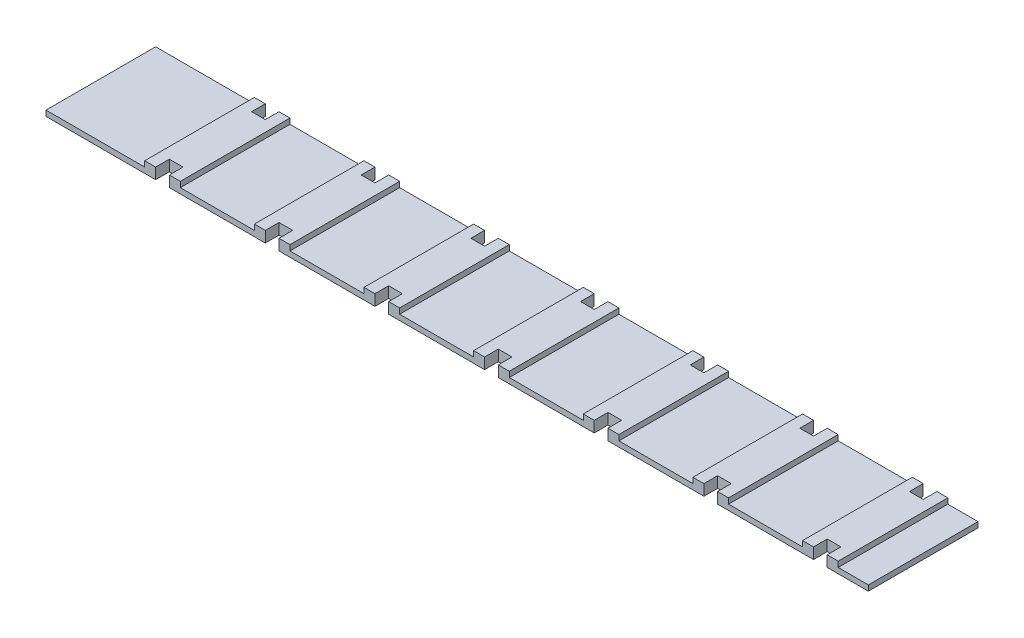
SolidWorks part; units mm, degrees
ref_plane "Front Plane" through (0, 0, 0) normal (0, 0, 1) x (1, 0, 0)
ref_plane "Top Plane" through (0, 0, 0) normal (0, 1, 0) x (1, 0, 0)
ref_plane "Right Plane" through (0, 0, 0) normal (1, 0, 0) x (0, 0, -1)
sketch "Sketch1" plane through (0, 0, 0) normal (0, 1, 0) x (1, 0, 0)
  line L0 (40, 0) -> (40, 2.5)
  line L1 (0, 0) -> (20, 0)
  line L2 (0, 0) -> (0, 20)
  line L3 (0, 20) -> (20, 20)
  line L4 (150, 0) -> (150, 20)
  line L6 (20, 20) -> (20, 17.5)
  line L7 (20, 17.5) -> (22.5, 17.5)
  line L8 (22.5, 20) -> (22.5, 17.5)
  line L10 (20, 0) -> (20, 2.5)
  line L11 (20, 2.5) -> (22.5, 2.5)
  line L12 (22.5, 0) -> (22.5, 2.5)
  line L14 (42.5, 0) -> (42.5, 2.5)
  line L15 (40, 2.5) -> (42.5, 2.5)
  line L16 (40, 20) -> (40, 17.5)
  line L18 (42.5, 20) -> (42.5, 17.5)
  line L19 (40, 17.5) -> (42.5, 17.5)
  line L20 (60, 0) -> (60, 2.5)
  line L22 (62.5, 0) -> (62.5, 2.5)
  line L23 (60, 2.5) -> (62.5, 2.5)
  line L24 (60, 20) -> (60, 17.5)
  line L26 (62.5, 20) -> (62.5, 17.5)
  line L27 (60, 17.5) -> (62.5, 17.5)
  line L28 (80, 0) -> (80, 2.5)
  line L30 (82.5, 0) -> (82.5, 2.5)
  line L31 (80, 2.5) -> (82.5, 2.5)
  line L32 (80, 20) -> (80, 17.5)
  line L34 (82.5, 20) -> (82.5, 17.5)
  line L35 (80, 17.5) -> (82.5, 17.5)
  line L36 (100, 0) -> (100, 2.5)
  line L38 (102.5, 0) -> (102.5, 2.5)
  line L39 (100, 2.5) -> (102.5, 2.5)
  line L40 (100, 20) -> (100, 17.5)
  line L42 (102.5, 20) -> (102.5, 17.5)
  line L43 (100, 17.5) -> (102.5, 17.5)
  line L44 (120, 0) -> (120, 2.5)
  line L46 (122.5, 0) -> (122.5, 2.5)
  line L47 (120, 2.5) -> (122.5, 2.5)
  line L48 (120, 20) -> (120, 17.5)
  line L50 (122.5, 20) -> (122.5, 17.5)
  line L51 (120, 17.5) -> (122.5, 17.5)
  line L52 (140, 0) -> (140, 2.5)
  line L54 (142.5, 0) -> (142.5, 2.5)
  line L55 (140, 2.5) -> (142.5, 2.5)
  line L56 (140, 20) -> (140, 17.5)
  line L58 (142.5, 20) -> (142.5, 17.5)
  line L59 (140, 17.5) -> (142.5, 17.5)
  line L60 (22.5, 0) -> (40, 0)
  line L61 (22.5, 20) -> (40, 20)
  line L62 (42.5, 20) -> (60, 20)
  line L63 (62.5, 20) -> (80, 20)
  line L64 (82.5, 20) -> (100, 20)
  line L65 (102.5, 20) -> (120, 20)
  line L66 (122.5, 20) -> (140, 20)
  line L67 (142.5, 20) -> (150, 20)
  line L68 (142.5, 0) -> (150, 0)
  line L69 (122.5, 0) -> (140, 0)
  line L70 (102.5, 0) -> (120, 0)
  line L71 (82.5, 0) -> (100, 0)
  line L72 (62.5, 0) -> (80, 0)
  line L73 (42.5, 0) -> (60, 0)
  dimension "D1" = 150
  dimension "D2" = 20
  dimension "D3" = 22.5
  dimension "D4" = 40
  dimension "D5" = 2.5
  dimension "D6" = 17.5
  dimension "D8" = 7
extrude "Boss-Extrude1" add sketch "Sketch1" along normal blind 1
sketch "Sketch2" plane through (0, 1, 0) normal (0, 1, 0) x (1, 0, 0)
  line L0 (20, 20) -> (18, 20)
  line L1 (20, 20) -> (0, 20) construction
  line L2 (18, 20) -> (18, 0)
  line L3 (0, 0) -> (20, 0) construction
  line L4 (18, 0) -> (20, 0)
  line L5 (20, 0) -> (20, 2.5)
  line L6 (20, 2.5) -> (22.5, 2.5)
  line L7 (22.5, 2.5) -> (22.5, 0)
  line L8 (22.5, 0) -> (24.5, 0)
  line L9 (22.5, 0) -> (40, 0) construction
  line L10 (24.5, 0) -> (24.5, 20)
  line L11 (40, 20) -> (22.5, 20) construction
  line L12 (24.5, 20) -> (22.5, 20)
  line L13 (22.5, 20) -> (22.5, 17.5)
  line L14 (22.5, 17.5) -> (20, 17.5)
  line L15 (20, 17.5) -> (20, 20) construction
  line L16 (22.5, 17.5) -> (20, 17.5) construction
  line L17 (20, 17.5) -> (20, 20)
  line L18 (40, 17.5) -> (40, 20)
  line L19 (40, 20) -> (38, 20)
  line L20 (38, 20) -> (38, 0)
  line L21 (38, 0) -> (40, 0)
  line L22 (40, 0) -> (40, 2.5)
  line L23 (40, 2.5) -> (42.5, 2.5)
  line L24 (42.5, 2.5) -> (42.5, 0)
  line L25 (42.5, 0) -> (44.5, 0)
  line L26 (44.5, 0) -> (44.5, 20)
  line L27 (44.5, 20) -> (42.5, 20)
  line L28 (42.5, 20) -> (42.5, 17.5)
  line L29 (42.5, 17.5) -> (40, 17.5)
  line L30 (60, 17.5) -> (60, 20)
  line L31 (60, 20) -> (58, 20)
  line L32 (58, 20) -> (58, 0)
  line L33 (58, 0) -> (60, 0)
  line L34 (60, 0) -> (60, 2.5)
  line L35 (60, 2.5) -> (62.5, 2.5)
  line L36 (62.5, 2.5) -> (62.5, 0)
  line L37 (62.5, 0) -> (64.5, 0)
  line L38 (64.5, 0) -> (64.5, 20)
  line L39 (64.5, 20) -> (62.5, 20)
  line L40 (62.5, 20) -> (62.5, 17.5)
  line L41 (62.5, 17.5) -> (60, 17.5)
  line L42 (80, 17.5) -> (80, 20)
  line L43 (80, 20) -> (78, 20)
  line L44 (78, 20) -> (78, 0)
  line L45 (78, 0) -> (80, 0)
  line L46 (80, 0) -> (80, 2.5)
  line L47 (80, 2.5) -> (82.5, 2.5)
  line L48 (82.5, 2.5) -> (82.5, 0)
  line L49 (82.5, 0) -> (84.5, 0)
  line L50 (84.5, 0) -> (84.5, 20)
  line L51 (84.5, 20) -> (82.5, 20)
  line L52 (82.5, 20) -> (82.5, 17.5)
  line L53 (82.5, 17.5) -> (80, 17.5)
  line L54 (100, 17.5) -> (100, 20)
  line L55 (100, 20) -> (98, 20)
  line L56 (98, 20) -> (98, 0)
  line L57 (98, 0) -> (100, 0)
  line L58 (100, 0) -> (100, 2.5)
  line L59 (100, 2.5) -> (102.5, 2.5)
  line L60 (102.5, 2.5) -> (102.5, 0)
  line L61 (102.5, 0) -> (104.5, 0)
  line L62 (104.5, 0) -> (104.5, 20)
  line L63 (104.5, 20) -> (102.5, 20)
  line L64 (102.5, 20) -> (102.5, 17.5)
  line L65 (102.5, 17.5) -> (100, 17.5)
  line L66 (120, 17.5) -> (120, 20)
  line L67 (120, 20) -> (118, 20)
  line L68 (118, 20) -> (118, 0)
  line L69 (118, 0) -> (120, 0)
  line L70 (120, 0) -> (120, 2.5)
  line L71 (120, 2.5) -> (122.5, 2.5)
  line L72 (122.5, 2.5) -> (122.5, 0)
  line L73 (122.5, 0) -> (124.5, 0)
  line L74 (124.5, 0) -> (124.5, 20)
  line L75 (124.5, 20) -> (122.5, 20)
  line L76 (122.5, 20) -> (122.5, 17.5)
  line L77 (122.5, 17.5) -> (120, 17.5)
  line L78 (140, 17.5) -> (140, 20)
  line L79 (140, 20) -> (138, 20)
  line L80 (138, 20) -> (138, 0)
  line L81 (138, 0) -> (140, 0)
  line L82 (140, 0) -> (140, 2.5)
  line L83 (140, 2.5) -> (142.5, 2.5)
  line L84 (142.5, 2.5) -> (142.5, 0)
  line L85 (142.5, 0) -> (144.5, 0)
  line L86 (144.5, 0) -> (144.5, 20)
  line L87 (144.5, 20) -> (142.5, 20)
  line L88 (142.5, 20) -> (142.5, 17.5)
  line L89 (142.5, 17.5) -> (140, 17.5)
  line L90 (0, 20) -> (0, 0) construction
  dimension "D1" = 2
  dimension "D2" = 2
  dimension "D4" = 38
  dimension "D3" = 7
extrude "Boss-Extrude2" add sketch "Sketch2" along normal blind 1
